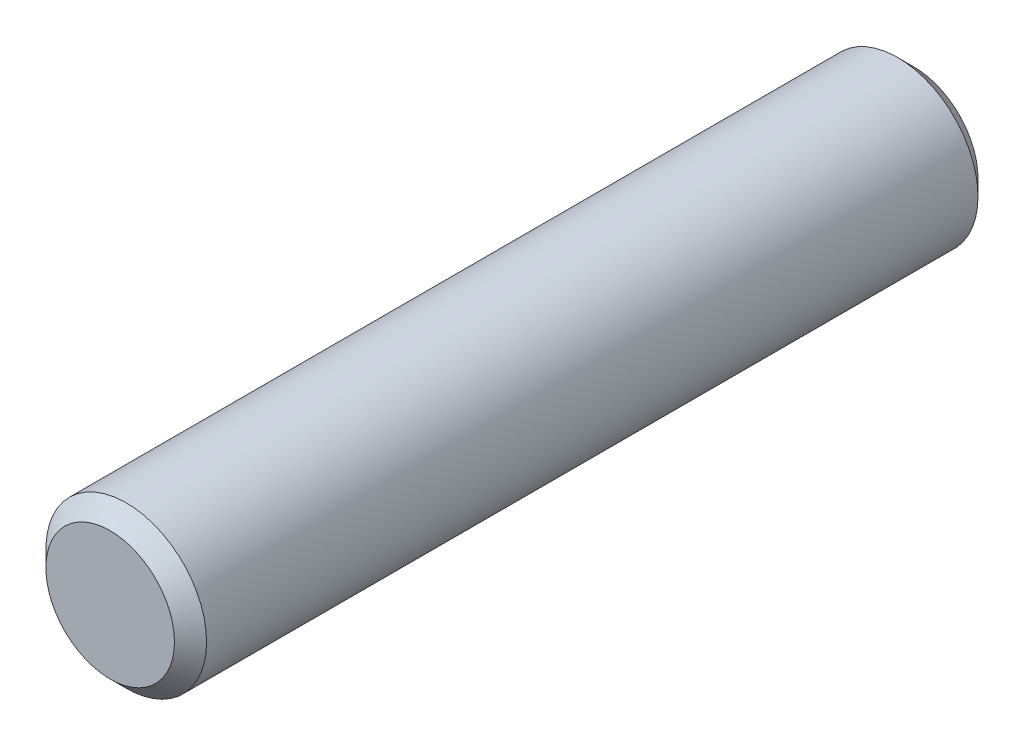
SolidWorks part; units mm, degrees
material "Alloy Steel"
ref_plane "Front Plane" through (0, 0, 0) normal (0, 0, 1) x (1, 0, 0)
ref_plane "Top Plane" through (0, 0, 0) normal (0, 1, 0) x (1, 0, 0)
ref_plane "Right Plane" through (0, 0, 0) normal (1, 0, 0) x (0, 0, -1)
sketch "Sketch1" plane through (0, 0, 0) normal (0, 0, 1) x (1, 0, 0)
  circle A0 centre (0, 0) radius 6.35
  dimension "D1" = 12.7
extrude "Boss-Extrude1" add sketch "Sketch1" against normal blind 63.5
chamfer "Chamfer1" distance 1.27 angle 45 2 edges at (6.35, 0, -63.5) (6.35, 0, 0)
